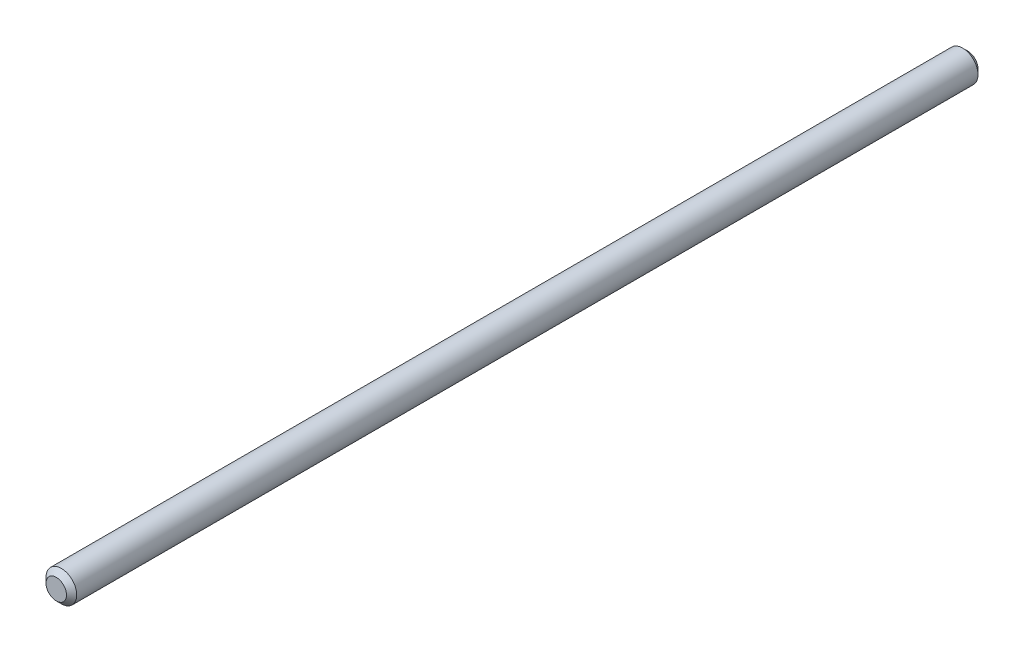
SolidWorks part; units mm, degrees
ref_plane "Front Plane" through (0, 0, 0) normal (0, 0, 1) x (1, 0, 0)
ref_plane "Top Plane" through (0, 0, 0) normal (0, 1, 0) x (1, 0, 0)
ref_plane "Right Plane" through (0, 0, 0) normal (1, 0, 0) x (0, 0, -1)
sketch "Sketch1" plane through (0, 0, 0) normal (0, 0, 1) x (1, 0, 0)
  circle A0 centre (0, 0) radius 3
  dimension "D1" = 6
extrude "Boss-Extrude1" add sketch "Sketch1" along normal mid plane 178
chamfer "Chamfer1" distance 1 angle 45 2 edges at (3, 0, -89) (3, 0, 89)
